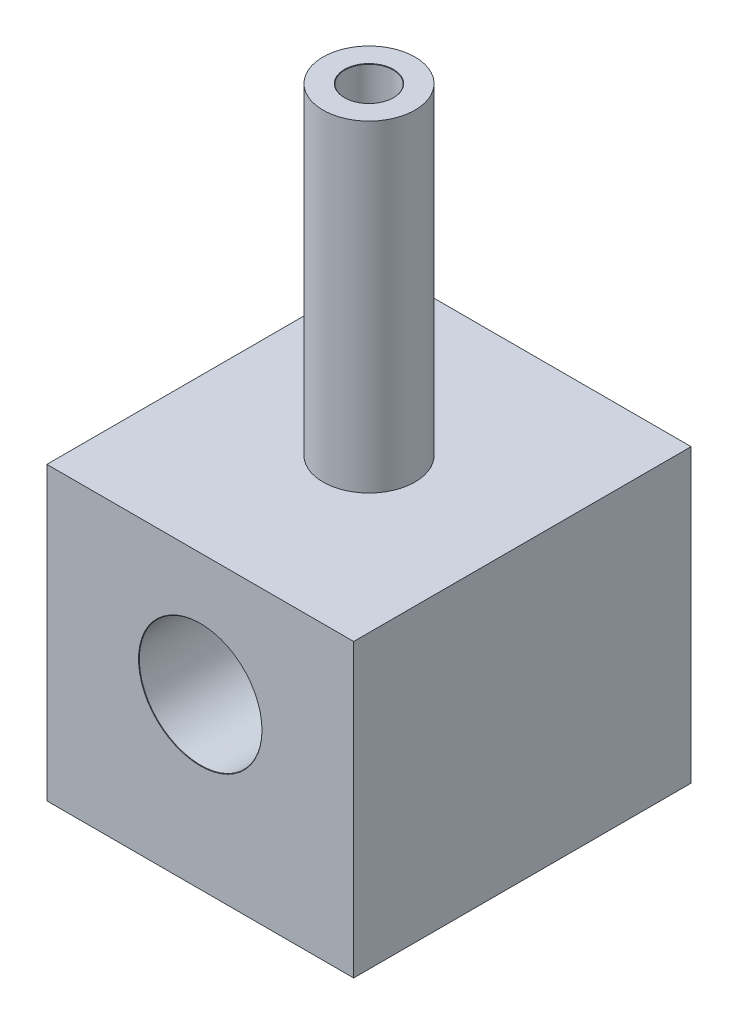
SolidWorks part; units mm, degrees
ref_plane "Front Plane" through (0, 0, 0) normal (0, 0, 1) x (1, 0, 0)
ref_plane "Top Plane" through (0, 0, 0) normal (0, 1, 0) x (1, 0, 0)
ref_plane "Right Plane" through (0, 0, 0) normal (1, 0, 0) x (0, 0, -1)
sketch "Sketch1" plane through (0, 0, 0) normal (0, 0, 1) x (1, 0, 0)
  circle A0 centre (0, 0) radius 10
  dimension "D1" = 20
extrude "Boss-Extrude1" add sketch "Sketch1" along normal blind 22
sketch "Sketch18" plane through (0, 0, 22) normal (0, 0, 1) x (1, 0, 0)
  point P0 (0, 0)
sketch "Sketch6" plane through (0, 0, 0) normal (0, 1, 0) x (1, 0, 0)
  line L0 (0, 0) -> (0, -22) construction
  line L1 (-10, -22) -> (10, -22) construction
  circle A0 centre (0, -11) radius 11
extrude "Boss-Extrude2" add sketch "Sketch6" along normal mid plane 22 contours A0
hole_wizard "Ø8.0mm Dowel Hole1" positions "Sketch18" profile "Sketch3" hole size "Ø8.0" standard "DIN" end condition through all
sketch "Sketch3" plane through (0, 0, 22) normal (1, 0, 0) x (0, -1, 0)
  line L0 (0, 0) -> (0, 22)
  line L1 (0, 22) -> (4, 22)
  line L2 (4, 22) -> (4, 0.025)
  line L3 (4, 0.025) -> (4.025, 0)
  line L5 (4.025, 0) -> (0, 0)
  line L6 (-4, 0.025) -> (-4.025, 0) construction
  line L11 (0, -6.35) -> (0, 107.95) construction
  dimension "Thru Hole Dia." = 8
  dimension "Thru Hole Depth" = 22
  dimension "Near C'Sink Dia." = 8.05
  dimension "Near C'Sink Angle" = 90
sketch "Sketch9" plane through (0, 11, 0) normal (0, 1, 0) x (1, 0, 0)
  circle A0 centre (0, -11) radius 15.7929
extrude "Cut-Extrude1" cut sketch "Sketch9" against normal blind 3
sketch "Sketch8" plane through (0, 8, 0) normal (0, 1, 0) x (1, 0, 0)
  circle A0 centre (0, -11) radius 3
  dimension "D1" = 6
extrude "Boss-Extrude3" add sketch "Sketch8" along normal blind 21
sketch "Sketch10" plane through (0, 8, 0) normal (0, 1, 0) x (1, 0, 0)
  line L0 (-6, -22) -> (-6, 0)
  line L1 (-10, 0) -> (-6, 0)
  line L2 (-10, 0) -> (-10, -22)
  line L3 (-10, -22) -> (-6, -22)
  line L4 (10, 0) -> (10, -22)
  line L5 (-6, 0) -> (-6, -1.7805) construction
  line L6 (6, 0) -> (6, -22)
  line L7 (6, -22) -> (10, -22)
  line L8 (6, 0) -> (10, 0)
extrude "Boss-Extrude4" add sketch "Sketch10" against normal up to surface (19 mm away) up to face at (0, -11, 22)
sketch "Sketch11" plane through (0, -11, 0) normal (0, -1, 0) x (1, 0, 0)
  line L1 (-10, 22) -> (10, 22)
  line L2 (-10, 22) -> (-10, 0)
  line L3 (-10, 0) -> (10, 0)
  line L4 (10, 22) -> (10, 0)
extrude "Boss-Extrude5" add sketch "Sketch11" against normal up to vertex
sketch "Sketch12" plane through (0, -11, 0) normal (0, -1, 0) x (1, 0, 0)
  line L0 (-13, 25) -> (-13, -3)
  line L1 (-10, 22) -> (10, 22)
  line L2 (-10, 22) -> (-10, 0)
  line L3 (-10, 0) -> (10, 0)
  line L4 (10, 22) -> (10, 0)
  line L5 (-13, -3) -> (13, -3)
  line L6 (13, 25) -> (13, -3)
  line L7 (-13, 25) -> (13, 25)
  dimension "D1" = 3
extrude "Cut-Extrude2" cut sketch "Sketch12" against normal through all
sketch "Sketch13" plane through (0, 0, 0) normal (1, 0, 0) x (0, 0, -1)
  line L0 (-11, 8) -> (-11, 32.3867) construction
  line L1 (-22, 8) -> (0, 8) construction
  line L2 (-8.5, 8) -> (-8.5, 14)
  line L3 (-13.5, 8) -> (-13.5, 14)
  line L4 (-13.5, 14) -> (-8.5, 14)
  line L5 (-8.5, 8) -> (-8.5, 32.3867) construction
  line L6 (-13.5, 8) -> (-13.5, 32.3867) construction
  line L7 (-14, 29) -> (-14, 8) construction
  line L9 (-14, 14) -> (-8, 14)
  line L10 (-14, 14) -> (-14, 8)
  line L11 (-14, 8) -> (-8, 8)
  line L12 (-8, 14) -> (-8, 8)
  point P10 (-14, 14)
  point P11 (-8, 8)
  dimension "D1" = 2.5
  dimension "D3" = 6
  dimension "D2" = 2.5
revolve "podciecie lozysko osiowe" [suppressed] cut sketch "Sketch13" angle 360 about L0
hole_wizard "Tap Drill for M3 Helicoil1" positions "Sketch17" profile "Sketch16" hole size "M3x0.5" standard "DIN"
sketch "Sketch17" plane through (0, 29, 0) normal (0, 1, 0) x (1, 0, 0)
  point P0 (0, -11)
sketch "Sketch16" plane through (0, 29, 11) normal (1, 0, 0) x (0, 0, 1)
  line L0 (0, 0) -> (0, 6.9464)
  line L1 (0, 6.9464) -> (1.575, 6)
  line L2 (1.575, 6) -> (1.575, 0.025)
  line L3 (1.575, 0.025) -> (1.6, 0)
  line L5 (1.6, 0) -> (0, 0)
  line L6 (-1.575, 0.025) -> (-1.6, 0) construction
  line L10 (0, 6.9464) -> (-1.575, 6) construction
  line L11 (0, -6.35) -> (0, 107.95) construction
  dimension "Hole Dia." = 3.15
  dimension "Hole Depth" = 6
  dimension "Near C'Sink Dia." = 3.2
  dimension "Near C'Sink Angle" = 90
  dimension "Drill Angle" = 118
